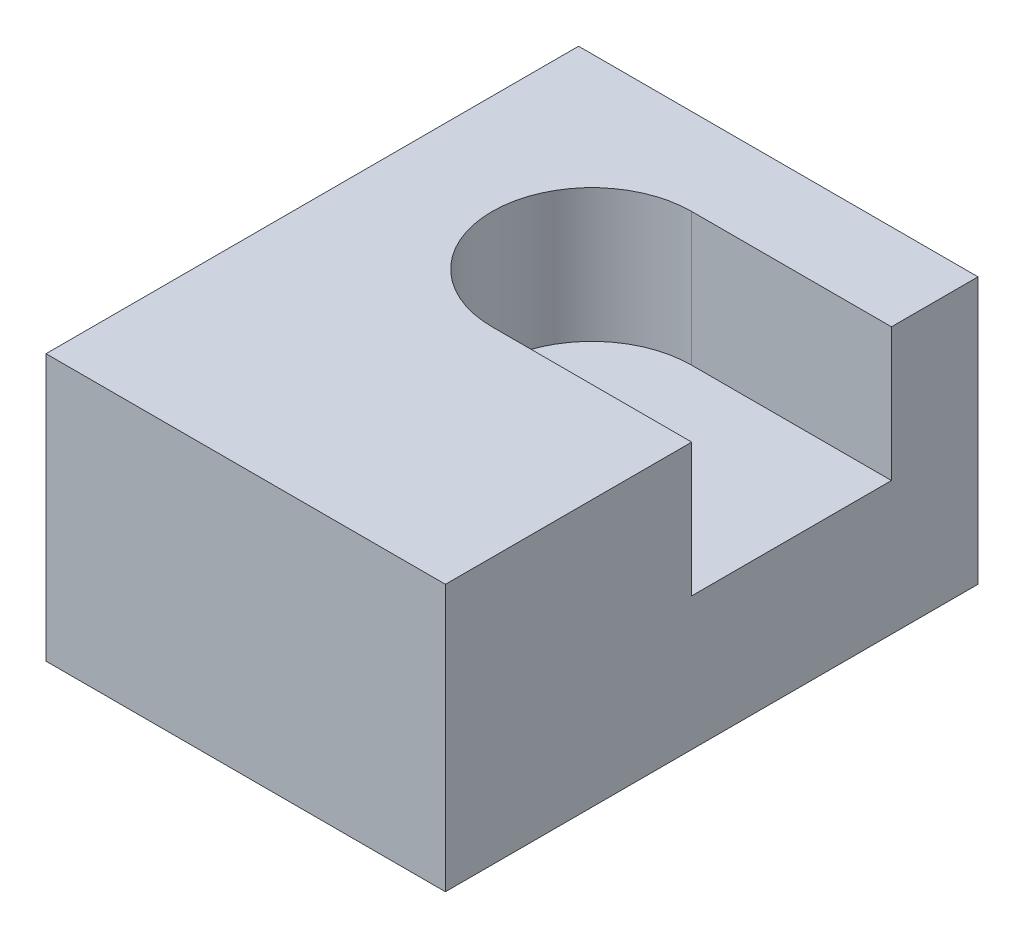
SolidWorks part; units mm, degrees
material "6061 Alloy"
ref_plane "Front Plane" through (0, 0, 0) normal (0, 0, 1) x (1, 0, 0)
ref_plane "Top Plane" through (0, 0, 0) normal (0, 1, 0) x (1, 0, 0)
ref_plane "Right Plane" through (0, 0, 0) normal (1, 0, 0) x (0, 0, -1)
sketch "Sketch1" plane through (0, 0, 0) normal (0, 0, 1) x (1, 0, 0)
  line L1 (-19.05, 12.7) -> (19.05, 12.7)
  line L2 (-19.05, 12.7) -> (-19.05, -12.7)
  line L3 (-19.05, -12.7) -> (19.05, -12.7)
  line L4 (19.05, 12.7) -> (19.05, -12.7)
  line L5 (-19.05, 12.7) -> (19.05, -12.7) construction
  line L6 (-19.05, -12.7) -> (19.05, 12.7) construction
  point P0 (0, 0)
  dimension "D1" = 38.1
  dimension "D2" = 25.4
extrude "Boss-Extrude1" add sketch "Sketch1" along normal blind 50.8
sketch "Sketch2" plane through (0, 12.7, 0) normal (0, 1, 0) x (1, 0, 0)
  line L0 (19.05, -8.255) -> (0, -8.255)
  line L1 (19.05, -50.8) -> (19.05, 0) construction
  line L2 (0, -27.305) -> (19.05, -27.305)
  line L3 (19.05, -27.305) -> (19.05, -8.255)
  line L4 (19.05, 0) -> (-19.05, 0) construction
  arc A0 (0, -8.255) -> (0, -27.305) centre (0, -17.78) ccw
  dimension "D1" = 9.525
  dimension "D2" = 19.05
  dimension "D3" = 17.78
extrude "Cut-Extrude1" cut sketch "Sketch2" against normal blind 12.7
